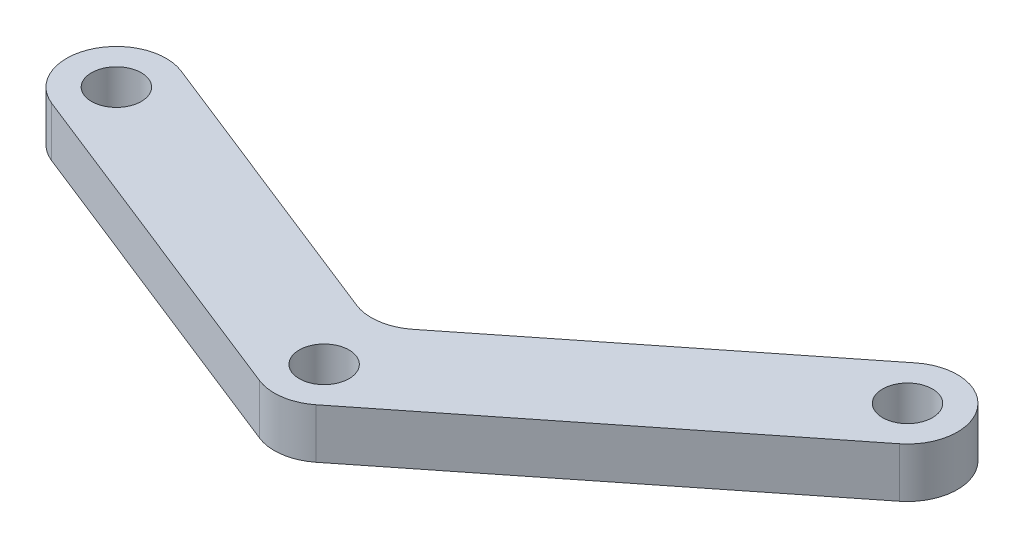
SolidWorks part; units mm, degrees
ref_plane "Front Plane" through (0, 0, 0) normal (0, 0, 1) x (1, 0, 0)
ref_plane "Top Plane" through (0, 0, 0) normal (0, 1, 0) x (1, 0, 0)
ref_plane "Right Plane" through (0, 0, 0) normal (1, 0, 0) x (0, 0, -1)
sketch "Sketch2" plane through (0, 0, 0) normal (0, 1, 0) x (1, 0, 0)
  line L0 (0, -12.5) -> (0, 12.5)
  line L1 (0, -12.5) -> (-25, -12.5)
  line L2 (0, 12.5) -> (25, 12.5)
  line L3 (0, 0) -> (-12.4066, 38.0273)
  line L4 (-12.4066, 38.0273) -> (-32, 22.5)
  line L5 (-32, 22.5) -> (-52.7065, 30.7)
  line L6 (-52.7065, 30.7) -> (-30.6151, 86.485)
  line L7 (-12, 27.5) -> (-10.6151, 91.485)
  line L8 (-32, 22.5) -> (-30.6151, 86.485) construction
  line L9 (-10.6151, 91.485) -> (-30.6151, 86.485)
  line L10 (0, -57.9364) -> (0, 57.9364) construction
  line L11 (0, 0) -> (12.4066, 38.0273)
  line L12 (32, 22.5) -> (30.6151, 86.485) construction
  line L13 (10.6151, 91.485) -> (30.6151, 86.485)
  line L14 (12, 27.5) -> (10.6151, 91.485)
  line L15 (52.7065, 30.7) -> (30.6151, 86.485)
  line L16 (32, 22.5) -> (52.7065, 30.7)
  line L17 (12.4066, 38.0273) -> (32, 22.5)
  line L18 (-25, -6.5) -> (-25, -46.5) construction
  line L19 (-15, -6.5) -> (-35, -6.5)
  line L20 (-15, -6.5) -> (-15, -46.5)
  line L21 (-15, -46.5) -> (-35, -46.5)
  line L22 (-35, -6.5) -> (-35, -46.5)
  circle A0 centre (25, 12.5) radius 1.5
  circle A1 centre (-25, -12.5) radius 1.5
  circle A2 centre (-12, 27.5) radius 1.5
  circle A3 centre (-32, 22.5) radius 1.5
  circle A4 centre (32, 22.5) radius 1.5
  circle A5 centre (12, 27.5) radius 1.5
  circle A6 centre (-25, -12.5) radius 9.2314
  point P15 (0, 0)
  dimension "D3" = 3
  dimension "D1" = 25
  dimension "D2" = 25
  dimension "D5" = 12.5
  dimension "D4" = 12.5
  dimension "D6" = 25
  dimension "D7" = 25
  dimension "D8" = 40
  dimension "D10" = 25
  dimension "D11" = 120
  dimension "D15" = 20
  dimension "D17" = 40
  dimension "D9" = 12
  dimension "D14" = 5
  dimension "D13" = 64
  dimension "D12" = 60
  dimension "D16" = 40
  dimension "D18" = 20
  dimension "D19" = 6
sketch "Sketch3" plane through (0, 0, 0) normal (0, 1, 0) x (1, 0, 0)
  line L2 (-52.7065, 30.7) -> (-30.6151, 86.485) construction
  line L4 (-14.2699, 40.3785) -> (-32.5058, 25.927)
  line L5 (-32.5058, 25.927) -> (-51.602, 33.4892)
  line L6 (-14.2699, 40.3785) -> (-31.1483, 27.0027)
  line L7 (-34.1162, 26.5647) -> (-51.602, 33.4892)
  line L8 (-10.5433, 35.6761) -> (-31.4942, 19.073)
  line L9 (-31.4942, 19.073) -> (-53.8111, 27.9107)
  line L10 (-10.5433, 35.6761) -> (-30.1367, 20.1488)
  line L11 (-33.1046, 19.7107) -> (-53.8111, 27.9107)
  arc A0 (-53.8111, 27.9107) -> (-51.602, 33.4892) centre (-52.7065, 30.7) cw
  arc A1 (-10.5433, 35.6761) -> (-14.2699, 40.3785) centre (-12.4066, 38.0273) ccw
  circle A5 centre (-32, 22.5) radius 1.5
  arc A6 (-30.1367, 20.1488) -> (-33.1046, 19.7107) centre (-32, 22.5) cw
  arc A7 (-31.1483, 27.0027) -> (-34.1162, 26.5647) centre (-33.0116, 29.354) cw
  circle A8 centre (-52.7065, 30.7) radius 1.5
  circle A9 centre (-12.4066, 38.0273) radius 1.5
  dimension "D3" = 3
  dimension "D4" = 3
  dimension "D1" = 3
  dimension "D2" = 3
extrude "Boss-Extrude1" add sketch "Sketch3" along normal blind 3
equation "\"a\"= \"b\" / 2"
equation "\"b\"= 25"
equation "\"D1@Sketch2\"=2*\"a\""
equation "\"D2@Sketch2\"=\"b\""
equation "\"D5@Sketch2\"=\"a\""
equation "\"D4@Sketch2\"=\"a\""
equation "\"D6@Sketch2\"=\"b\""
equation "\"D7@Sketch2\"=\"b\""
equation "\"c\"= 64"
equation "\"D13@Sketch2\"=\"c\""
equation "\"D12@Sketch2\"=\"c\"-4"
